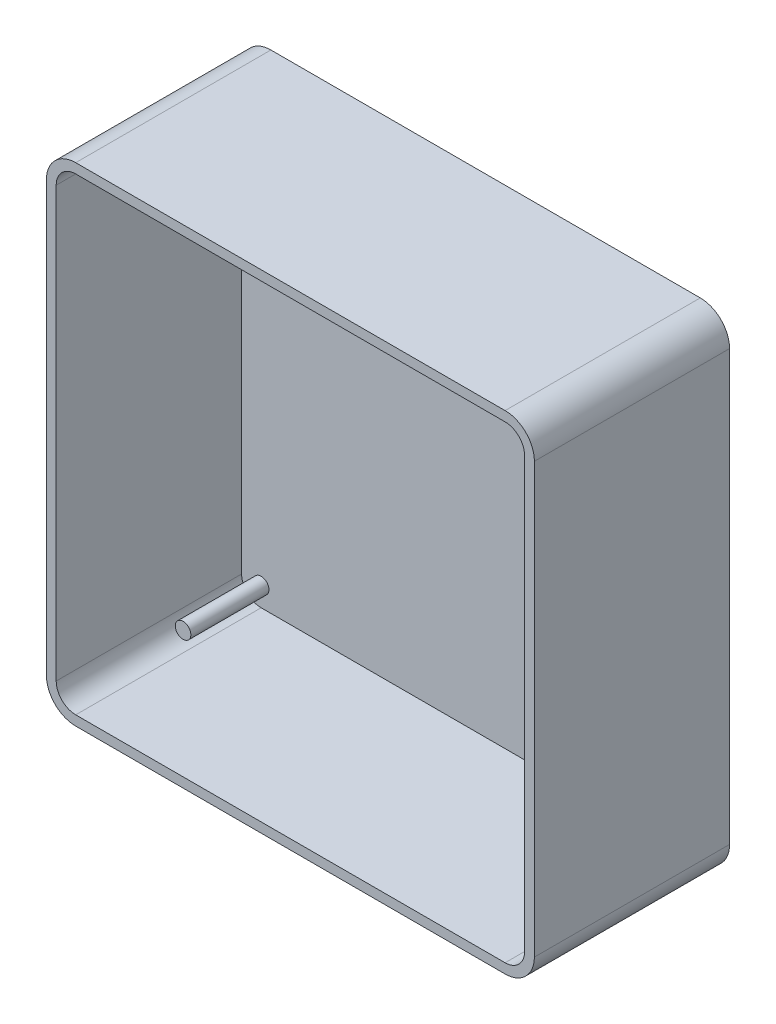
SolidWorks part; units mm, degrees
ref_plane "前视基准面" through (0, 0, 0) normal (0, 0, 1) x (1, 0, 0)
ref_plane "上视基准面" through (0, 0, 0) normal (0, 1, 0) x (1, 0, 0)
ref_plane "右视基准面" through (0, 0, 0) normal (1, 0, 0) x (0, 0, -1)
other "Configuration Table"
sketch "草图1" plane through (0, 0, 0) normal (0, 0, 1) x (1, 0, 0)
  line L1 (22, 25) -> (-22, 25)
  line L2 (25, 22) -> (25, -22)
  line L3 (22, -25) -> (-22, -25)
  line L4 (-25, 22) -> (-25, -22)
  line L5 (25, 25) -> (-25, -25) construction
  line L6 (25, -25) -> (-25, 25) construction
  arc A0 (25, 22) -> (22, 25) centre (22, 22) ccw
  arc A1 (22, -25) -> (25, -22) centre (22, -22) ccw
  arc A2 (-22, -25) -> (-25, -22) centre (-22, -22) cw
  arc A3 (-25, 22) -> (-22, 25) centre (-22, 22) cw
  point P0 (0, 0)
  dimension "D3" = 3
  dimension "D4" = 3
  dimension "D5" = 3
  dimension "D6" = 3
  dimension "D1" = 50
  dimension "D2" = 50
extrude "凸台-拉伸4" add sketch "草图1" along normal blind 1 contours L1 A3 L4 A2 L3 A1 L2 A0
sketch "草图7" plane through (0, 0, 1) normal (0, 0, 1) x (1, 0, 0)
  line L0 (25, -22) -> (25, 22)
  line L1 (22, 25) -> (-22, 25)
  line L2 (-25, 22) -> (-25, -22)
  line L26 (-22, -24) -> (22, -24)
  line L27 (24, -22) -> (24, 22)
  line L28 (-24, 22) -> (-24, -22)
  line L29 (22, 24) -> (-22, 24)
  line L30 (-22, -24) -> (22, -24)
  line L31 (24, -22) -> (24, 22)
  line L32 (-24, 22) -> (-24, -22)
  line L33 (22, 24) -> (-22, 24)
  arc A0 (25, 22) -> (22, 25) centre (22, 22) ccw
  arc A1 (-22, 25) -> (-25, 22) centre (-22, 22) ccw
  arc A20 (-24, -22) -> (-22, -24) centre (-22, -22) ccw
  arc A21 (22, -24) -> (24, -22) centre (22, -22) ccw
  arc A22 (24, 22) -> (22, 24) centre (22, 22) ccw
  arc A23 (-22, 24) -> (-24, 22) centre (-22, 22) ccw
  arc A24 (-24, -22) -> (-22, -24) centre (-22, -22) ccw
  arc A25 (22, -24) -> (24, -22) centre (22, -22) ccw
  arc A26 (24, 22) -> (22, 24) centre (22, 22) ccw
  arc A27 (-22, 24) -> (-24, 22) centre (-22, 22) ccw
  dimension "D1" = 1
  dimension "D2" = 1
extrude "凸台-拉伸5" add sketch "草图7" along normal blind 19 contours L0 L30 A25 L31 A26 L32 A27 L33 A24
sketch "草图12" plane through (0, 0, 1) normal (0, 0, 1) x (1, 0, 0)
  line L0 (22, 25) -> (-22, 25) construction
  line L3 (-25, 22) -> (-25, -22) construction
  circle A0 centre (-22, 22) radius 0.8
  point P4 (0, 0)
  point P6 (-22.9356, 22.9751)
  dimension "D1" = 1.6
  dimension "D2" = 3
  dimension "D3" = 3
extrude "凸台-拉伸7" add sketch "草图12" along normal blind 8
sketch "草图13" plane through (0, 0, 9) normal (0, 0, 1) x (1, 0, 0)
  circle A0 centre (-22, 22) radius 0.5
  circle A1 centre (-22, 22) radius 0.8 construction
  dimension "D1" = 0
extrude "切除-拉伸1" cut sketch "草图13" against normal blind 3
pattern_linear "阵列(线性)1" count 2 spacing 44 along (1, 0, 0) count 2 spacing 44 along (0, -1, 0) of "凸台-拉伸7"
pattern_linear "阵列(线性)2" count 2 spacing 44 count 2 spacing 44 along (1, 0, 0) of "切除-拉伸1"
